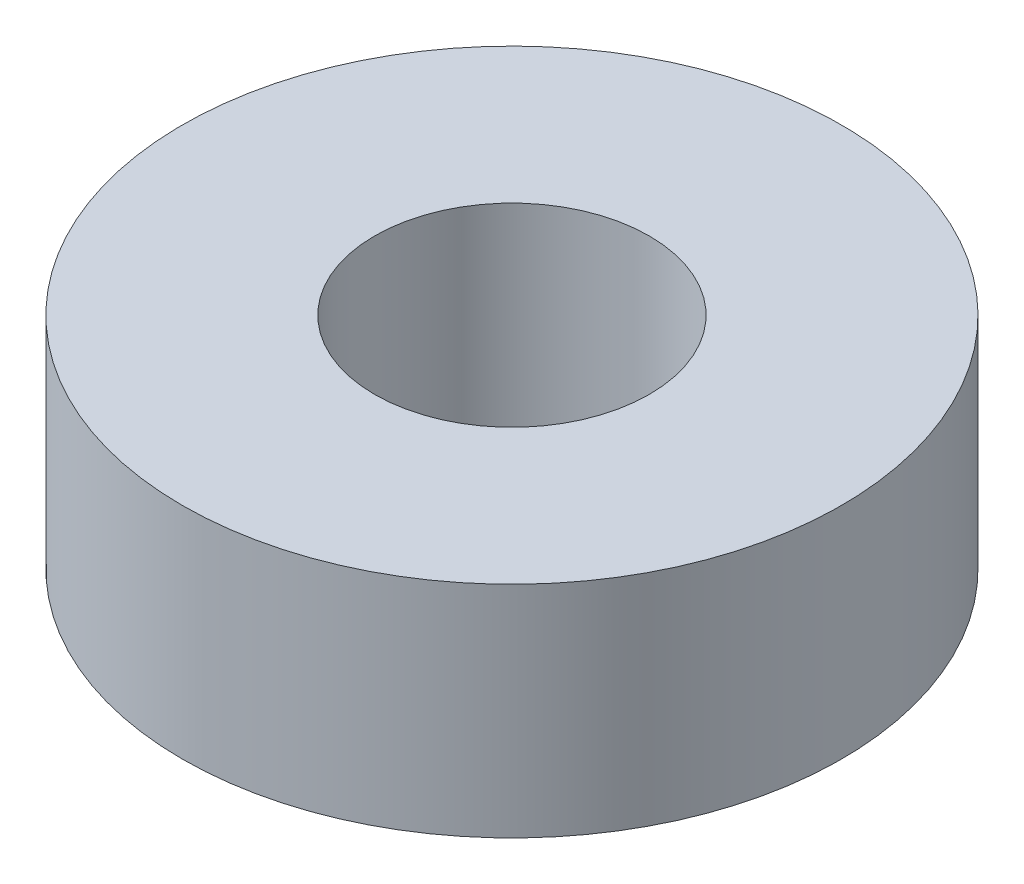
SolidWorks part; units mm, degrees
ref_plane "前视基准面" through (0, 0, 0) normal (0, 0, 1) x (1, 0, 0)
ref_plane "上视基准面" through (0, 0, 0) normal (0, 1, 0) x (1, 0, 0)
ref_plane "右视基准面" through (0, 0, 0) normal (1, 0, 0) x (0, 0, -1)
sketch "草图1" plane through (0, 0, 0) normal (0, 1, 0) x (1, 0, 0)
  circle A0 centre (0, 0) radius 2.5
  circle A1 centre (0, 0) radius 6
  dimension "D1" = 5
  dimension "D2" = 12
extrude "凸台-拉伸1" add sketch "草图1" along normal blind 4
